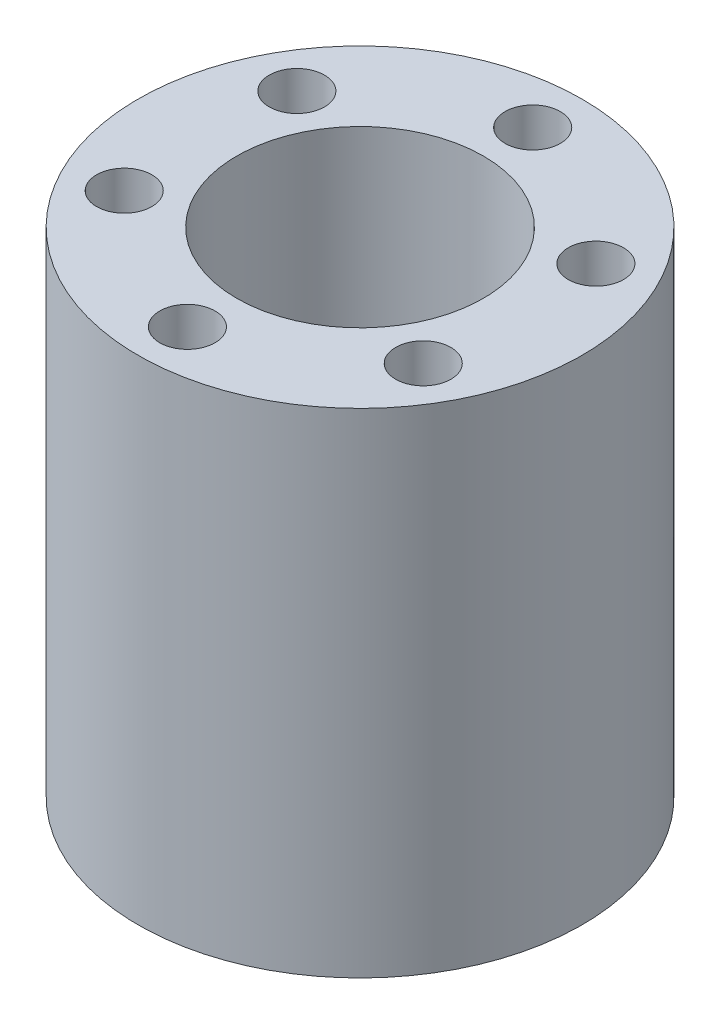
SolidWorks part; units mm, degrees
ref_plane "Ebene vorne" through (0, 0, 0) normal (0, 0, 1) x (1, 0, 0)
ref_plane "Ebene oben" through (0, 0, 0) normal (0, 1, 0) x (1, 0, 0)
ref_plane "Ebene rechts" through (0, 0, 0) normal (1, 0, 0) x (0, 0, -1)
sketch "Sketch2" plane through (0, 0, 0) normal (0, 0, 1) x (1, 0, 0)
  line L0 (0, 0) -> (0, 50) construction
  line L1 (12.5, 0) -> (12.5, 25)
  line L2 (12.5, 25) -> (22.5, 25)
  line L3 (22.5, 25) -> (22.5, 0)
  line L4 (22.5, 0) -> (12.5, 0)
  dimension "D1" = 50
  dimension "D2" = 45
  dimension "D3" = 25
  dimension "D4" = 25
revolve "Revolve1" add sketch "Sketch2" angle 360 about L0
hole_wizard "Ø5.6 (5.6) Diameter Hole1" positions "Sketch3" profile "Sketch5" hole size "Ø5.6" standard "DIN"
sketch "Sketch3" plane through (0, 25, 0) normal (0, 1, 0) x (1, 0, 0)
  line L0 (0, -12.5) -> (0, -22.5) construction
  circle A0 centre (0, 0) radius 12.5 construction
  circle A1 centre (0, 0) radius 22.5 construction
  point P9 (0, -17.5)
  point P17 (-15.1554, -8.75)
  point P18 (-15.1554, 8.75)
  point P19 (0, 17.5)
  point P20 (15.1554, 8.75)
  point P21 (15.1554, -8.75)
  dimension "D1" = 6
sketch "Sketch5" plane through (15.1554, 25, 8.75) normal (1, 0, 0) x (0, 0, 1)
  line L0 (0, 0) -> (0, 9.6824)
  line L1 (0, 9.6824) -> (2.8, 8)
  line L2 (2.8, 8) -> (2.8, 0)
  line L5 (2.8, 0) -> (0, 0)
  line L10 (0, 9.6824) -> (-2.8, 8) construction
  line L11 (0, -6.35) -> (0, 107.95) construction
  dimension "Hole Dia." = 5.6
  dimension "Hole Depth" = 8
  dimension "Drill Angle" = 118
mirror "Mirror1" about plane through (0, 0, 0) normal (0, 1, 0) of "Revolve1", "Ø5.6 (5.6) Diameter Hole1"
